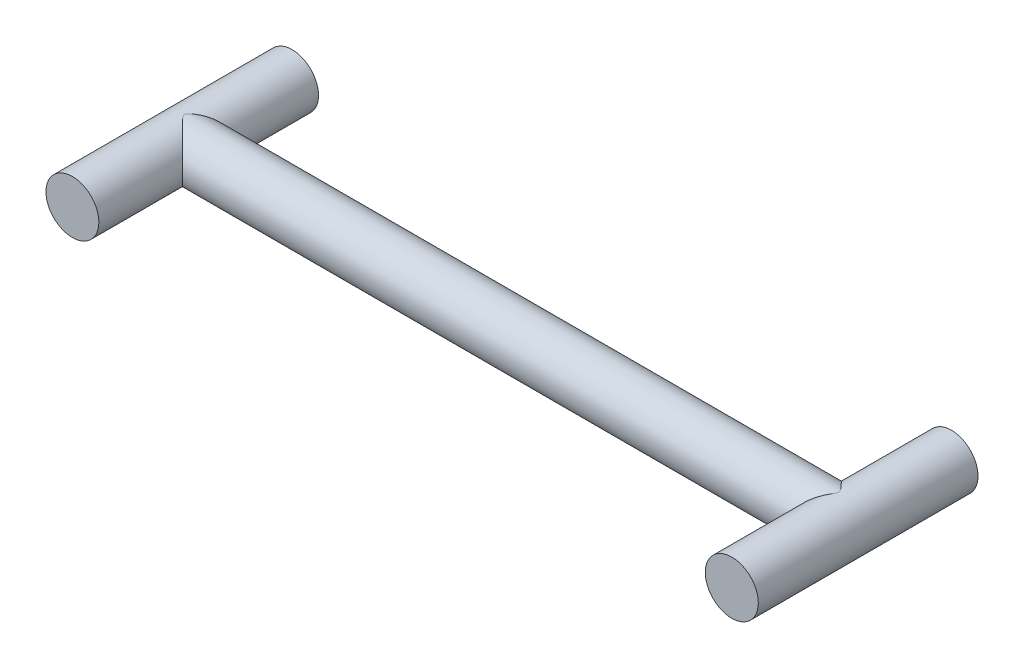
SolidWorks part; units mm, degrees
material "AISI 304"
ref_plane "前视基准面" through (0, 0, 0) normal (0, 0, 1) x (1, 0, 0)
ref_plane "上视基准面" through (0, 0, 0) normal (0, 1, 0) x (1, 0, 0)
ref_plane "右视基准面" through (0, 0, 0) normal (1, 0, 0) x (0, 0, -1)
sketch "草图1" plane through (0, 0, 0) normal (1, 0, 0) x (0, 0, -1)
  circle A0 centre (0, 0) radius 0.6
  dimension "D1" = 1.2
extrude "凸台-拉伸1" add sketch "草图1" along normal blind 15
sketch "草图2" plane through (0, 0, 0) normal (0, 0, 1) x (1, 0, 0)
  circle A0 centre (15.0082, 0) radius 0.6038
  circle A1 centre (0, 0) radius 0.6021
extrude "凸台-拉伸2" add sketch "草图2" along normal mid plane 5
